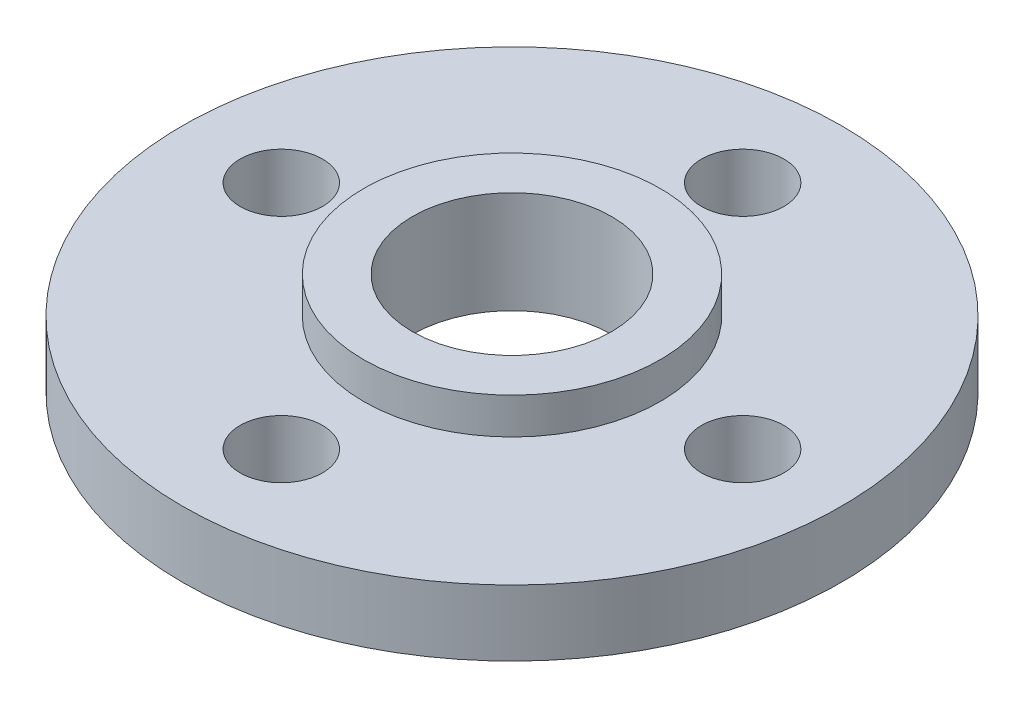
SolidWorks part; units mm, degrees
ref_plane "前视基准面" through (0, 0, 0) normal (0, 0, 1) x (1, 0, 0)
ref_plane "上视基准面" through (0, 0, 0) normal (0, 1, 0) x (1, 0, 0)
ref_plane "右视基准面" through (0, 0, 0) normal (1, 0, 0) x (0, 0, -1)
sketch "草图1" plane through (0, 0, 0) normal (0, 1, 0) x (1, 0, 0)
  circle A0 centre (0, 0) radius 10
  dimension "D1" = 20
extrude "凸台-拉伸1" add sketch "草图1" along normal blind 2
sketch "草图2" plane through (0, 2, 0) normal (0, 1, 0) x (1, 0, 0)
  circle A0 centre (0, 0) radius 4.5
  dimension "D1" = 9
extrude "凸台-拉伸2" add sketch "草图2" along normal blind 1.1
sketch "草图3" plane through (0, 3.1, 0) normal (0, 1, 0) x (1, 0, 0)
  circle A0 centre (0, 0) radius 3.025
  dimension "D1" = 6.05
extrude "切除-拉伸1" cut sketch "草图3" against normal up to next
sketch "草图4" plane through (0, 2, 0) normal (0, 1, 0) x (1, 0, 0)
  line L0 (-16.3816, 0) -> (16.2968, 0) construction
  line L1 (0, 15.6205) -> (0, -15.7085) construction
  circle A0 centre (0, 7) radius 1.25
  circle A1 centre (7, 0) radius 1.25
  circle A2 centre (0, -7) radius 1.25
  circle A3 centre (-7, 0) radius 1.25
  point P16 (0, 0)
  dimension "D1" = 2.5
  dimension "D2" = 7
  dimension "D3" = 4
extrude "切除-拉伸2" cut sketch "草图4" against normal up to next
